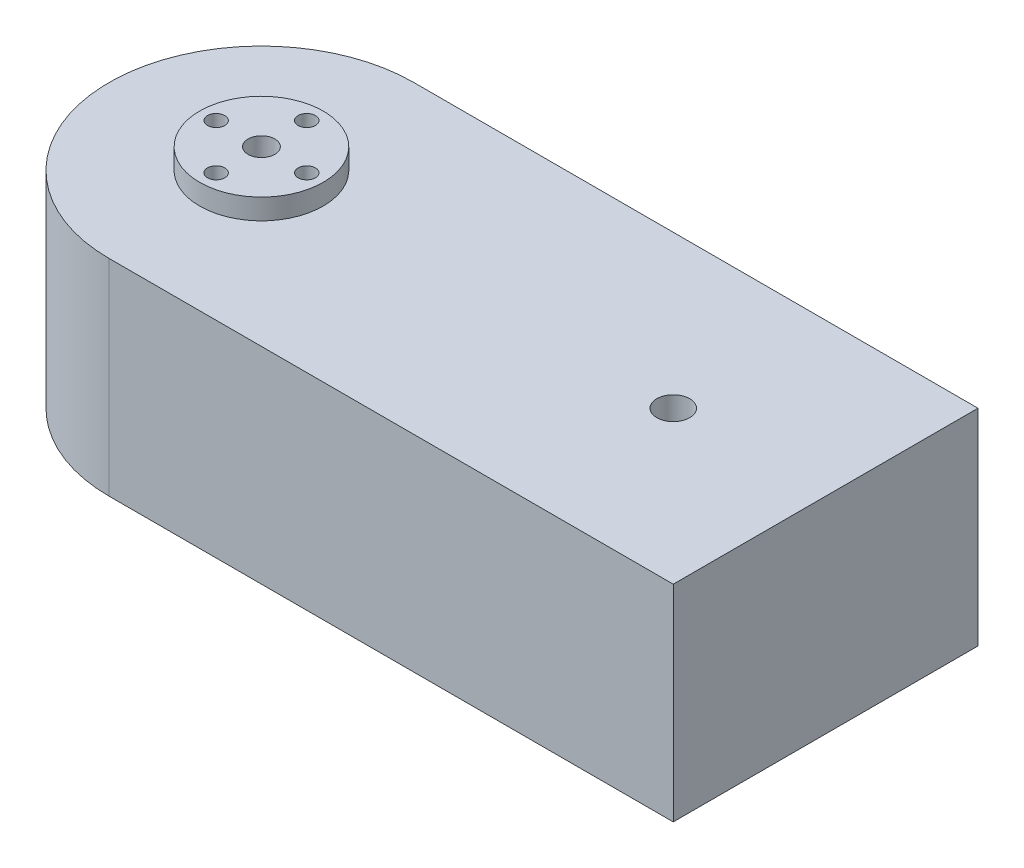
SolidWorks part; units mm, degrees
ref_plane "Front Plane" through (0, 0, 0) normal (0, 0, 1) x (1, 0, 0)
ref_plane "Top Plane" through (0, 0, 0) normal (0, 1, 0) x (1, 0, 0)
ref_plane "Right Plane" through (0, 0, 0) normal (1, 0, 0) x (0, 0, -1)
sketch "Sketch1" plane through (0, 0, 0) normal (0, 1, 0) x (1, 0, 0)
  line L0 (0, 37) -> (100, 37)
  line L1 (100, 37) -> (136.9979, 37)
  line L2 (100, -37) -> (0, -37)
  line L3 (136.9979, 37) -> (136.9979, -37)
  line L4 (136.9979, -37) -> (100, -37)
  arc A2 (0, 37) -> (0, -37) centre (0, 0) ccw
extrude "Boss-Extrude3" add sketch "Sketch1" along normal blind 10
sketch "Sketch4" plane through (0, 10, 0) normal (0, 1, 0) x (1, 0, 0)
  circle A0 centre (0, 0) radius 15
extrude "Boss-Extrude4" add sketch "Sketch4" along normal blind 5
sketch "Sketch5" plane through (0, 0, 0) normal (0, -1, 0) x (1, 0, 0)
  circle A0 centre (0, 0) radius 15
  circle A1 centre (0, 11) radius 2.1
  circle A2 centre (-11, 0) radius 2.1
  circle A3 centre (11, 0) radius 2.1
  circle A4 centre (0, -11) radius 2.1
  circle A8 centre (100, 0) radius 4
  circle A9 centre (0, 0) radius 3.25
  dimension "D1" = 4.2
  dimension "D2" = 4.2
  dimension "D3" = 4.2
  dimension "D4" = 4.2
sketch "Sketch7" plane through (0, 0, 0) normal (0, -1, 0) x (1, 0, 0)
  line L2 (0, 33) -> (133, 33)
  line L3 (133, 33) -> (133, -33)
  line L4 (133, -33) -> (0, -33)
  arc A0 (0, 33) -> (0, -33) centre (0, 0) ccw
  line M1 (136.9979, -37) -> (136.9979, 37)
  line M2 (136.9979, 37) -> (0, 37)
  arc M3 (0, 37) -> (0, -37) centre (0, 0) ccw
  line M4 (0, -37) -> (136.9979, -37)
extrude "Boss-Extrude5" add sketch "Sketch7" along normal blind 40 contours A0 L2 L3 L4 M4 M1 M2 M3
sketch "Sketch8" plane through (0, 0, 0) normal (0, -1, 0) x (1, 0, 0)
  line L0 (83.5, -30.5) -> (83.5, -33)
  line L2 (116.5, -30.5) -> (116.5, -33)
  line L3 (133, -33) -> (0, -33) construction
  line L4 (116.5, -33) -> (83.5, -33)
  line L5 (0, 33) -> (133, 33) construction
  line L6 (83.5, 24) -> (83.5, 33)
  line L7 (83.5, 33) -> (83.5, 14.75)
  line L8 (83.5, 14.75) -> (100, 14.75)
  line L9 (83.5, 33) -> (116.5, 33)
  line L13 (100, -14.75) -> (116.5, -14.75)
  line L14 (116.5, -14.75) -> (116.5, -30.5)
  line L15 (100, -14.75) -> (83.5, -14.75)
  line L16 (83.5, -14.75) -> (83.5, -30.5)
  line L17 (100, 14.75) -> (116.5, 14.75)
  line L18 (116.5, 14.75) -> (116.5, 33)
  circle A1 centre (100, 0) radius 6.1
  circle A2 centre (100, 24) radius 6.1
  circle A3 centre (100, -24) radius 6.1
  line M2 (133, 33) -> (0, 33)
  line M4 (0, -33) -> (133, -33)
extrude "Boss-Extrude10" add sketch "Sketch8" along normal blind 10 contours L17 L18 L6 L7 L8 A2 M2 | L15 L16 L0 L2 L14 L13 A3 M4
sketch "Sketch12" plane through (0, -10, 0) normal (0, -1, 0) x (1, 0, 0)
  line L0 (90, -14.75) -> (83.5, -14.75)
  line L1 (83.5, -14.75) -> (83.5, -33)
  line L2 (90, 24) -> (90, 33)
  line L3 (116.5, 33) -> (83.5, 33) construction
  line L4 (90, 33) -> (90, 14.75)
  line L5 (83.5, 14.75) -> (116.5, 14.75) construction
  line L6 (110, 24) -> (110, 33)
  line L7 (110, 33) -> (110, 14.75)
  line L8 (90, -24) -> (90, -14.75)
  line L9 (116.5, -14.75) -> (83.5, -14.75) construction
  line L10 (90, -14.75) -> (90, -33)
  line L11 (83.5, -33) -> (116.5, -33) construction
  line L12 (110, -24) -> (110, -33)
  line L13 (110, -33) -> (110, -14.75)
  line L14 (83.5, -33) -> (90, -33)
  line L15 (110, -33) -> (116.5, -33)
  line L16 (116.5, -33) -> (116.5, -14.75)
  line L17 (116.5, -14.75) -> (110, -14.75)
  line M2 (83.5, 14.75) -> (116.5, 14.75)
  line M3 (116.5, 14.75) -> (116.5, 33)
  line M4 (116.5, 33) -> (83.5, 33)
  line M5 (83.5, 33) -> (83.5, 14.75)
extrude "Boss-Extrude12" add sketch "Sketch12" along normal blind 25.25 contours L4 L2 M4 M5 M2 | L6 L7 M2 M3 M4 | L16 L17 L13 L12 L15 | L1 L14 L10 L8 L0
sketch "Sketch9" plane through (0, 0, 33) normal (0, 0, -1) x (-1, 0, 0)
  line L0 (-133, -40) -> (-133, -35)
  line L1 (-133, -35) -> (-83.5, -35)
  line L2 (-133, -40) -> (-133, 0) construction
  line L3 (-133, -35) -> (-133, 0)
  line L4 (-83.5, -35.25) -> (-83.5, 0) construction
  line L5 (-83.5, -35) -> (-83.5, -40)
  line L7 (0, -40) -> (-133, -40) construction
  line M5 (-133, 0) -> (-133, -40)
  line M6 (-133, -40) -> (0, -40)
  line M22 (-116.5, -35.25) -> (-116.5, 0)
  line M23 (-110, -10) -> (-110, -35.25)
  line M24 (-110, -35.25) -> (-116.5, -35.25)
  line M25 (-83.5, -35.25) -> (-90, -35.25)
  line M26 (-90, -35.25) -> (-90, -10)
extrude "Boss-Extrude13" add sketch "Sketch9" along normal blind 18.25 contours L5 L1 M25 M26 M23 M24 M22 M5 M6
sketch "Sketch13" plane through (0, 0, -33) normal (0, 0, 1) x (1, 0, 0)
  line L0 (133, -40) -> (133, -35)
  line L1 (133, -40) -> (133, 0) construction
  line L2 (133, -35) -> (83.5, -35)
  line L3 (83.5, -35.25) -> (83.5, 0) construction
  line L4 (83.5, -35) -> (83.5, -40)
  line L5 (133, -40) -> (0, -40) construction
  line L6 (83.5, -40) -> (133, -40)
extrude "Boss-Extrude14" add sketch "Sketch13" along normal blind 18.25
extrude "Cut-Extrude5" cut sketch "Sketch5" against normal blind 18.25 contours A2 | A9 | A1 | A3 | A4 | A8
sketch "Sketch14" plane through (0, 0, 0) normal (0, -1, 0) x (1, 0, 0)
  circle A0 centre (100, 24) radius 5.2
  circle A1 centre (100, -24) radius 5.2
  dimension "D1" = 10.4
  dimension "D2" = 10.4
extrude "Boss-Extrude15" add sketch "Sketch14" along normal blind 10
